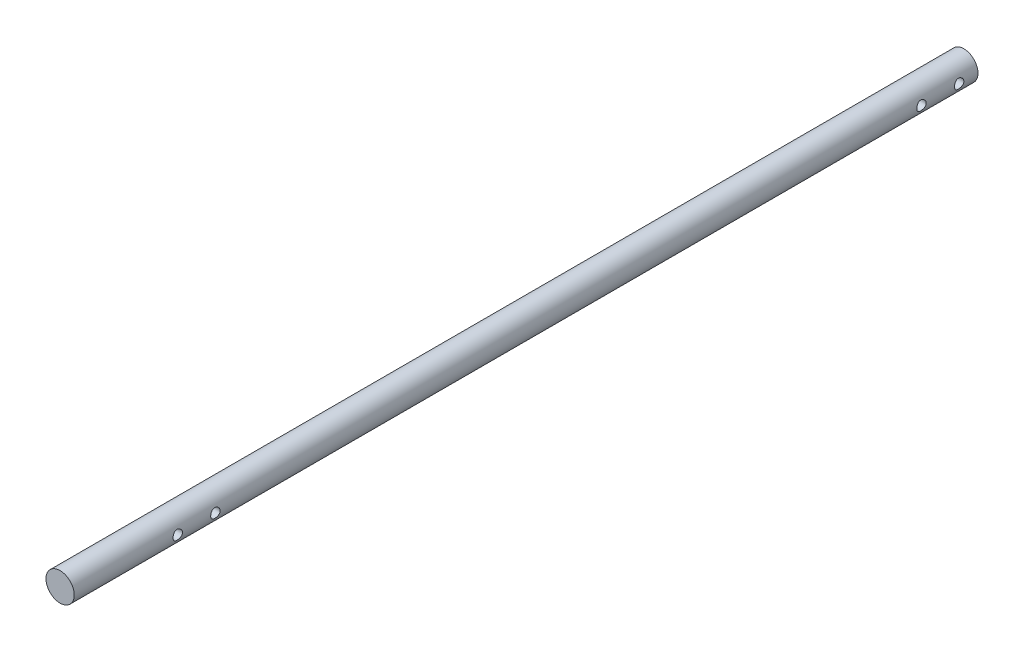
SolidWorks part; units mm, degrees
material "Cast Stainless Steel"
ref_plane "Front Plane" through (0, 0, 0) normal (0, 0, 1) x (1, 0, 0)
ref_plane "Top Plane" through (0, 0, 0) normal (0, 1, 0) x (1, 0, 0)
ref_plane "Right Plane" through (0, 0, 0) normal (1, 0, 0) x (0, 0, -1)
sketch "Sketch1" plane through (0, 0, 0) normal (0, 0, 1) x (1, 0, 0)
  circle A0 centre (0, 0) radius 9.525
extrude "Boss-Extrude1" add sketch "Sketch1" along normal blind 609.6
hole_wizard "1/4 (0.25) Diameter Hole1" positions "3DSketch4" profile "Sketch5" hole size "1/4" standard "ANSI Inch"
sketch3d "3DSketch4"
  line L0 (-12.7, 0, 514.35) -> (-9.525, 0, 514.35) construction
  line L1 (-12.7, 0, 539.75) -> (-9.525, 0, 539.75) construction
  circle A0 centre (-12.7, 0, 514.35) radius 3.175 construction
  point P0 (-12.7, 0, 511.175)
  point P4 (-9.525, 0, 514.35)
  point P5 (-12.7, 0, 514.35)
  point P9 (-12.7, 0, 539.75)
sketch "Sketch5" plane through (-12.7, 0, 514.35) normal (0, 1, 0) x (0, 0, 1)
  line L0 (0, 0) -> (0, 27.3067)
  line L1 (0, 27.3067) -> (3.175, 25.399)
  line L2 (3.175, 25.399) -> (3.175, 0)
  line L5 (3.175, 0) -> (0, 0)
  line L10 (0, 27.3067) -> (-3.175, 25.399) construction
  line L11 (0, -6.35) -> (0, 107.95) construction
  dimension "Hole Dia." = 6.35
  dimension "Hole Depth" = 25.399
  dimension "Drill Angle" = 118
hole_wizard "1/4 (0.25) Diameter Hole2" positions "3DSketch5" profile "Sketch6" hole size "1/4" standard "ANSI Inch"
sketch3d "3DSketch5"
  line L0 (-12.7, 0, 38.1) -> (-9.525, 0, 38.1) construction
  line L1 (-12.7, 0, 12.7) -> (-9.525, 0, 12.7) construction
  point P0 (-12.7, 0, 38.1)
  point P4 (-12.7, 0, 12.7)
sketch "Sketch6" plane through (-12.7, 0, 38.1) normal (0, 1, 0) x (0, 0, 1)
  line L0 (0, 0) -> (0, 27.3077)
  line L1 (0, 27.3077) -> (3.175, 25.4)
  line L2 (3.175, 25.4) -> (3.175, 0)
  line L5 (3.175, 0) -> (0, 0)
  line L10 (0, 27.3077) -> (-3.175, 25.4) construction
  line L11 (0, -6.35) -> (0, 107.95) construction
  dimension "Hole Dia." = 6.35
  dimension "Hole Depth" = 25.4
  dimension "Drill Angle" = 118
